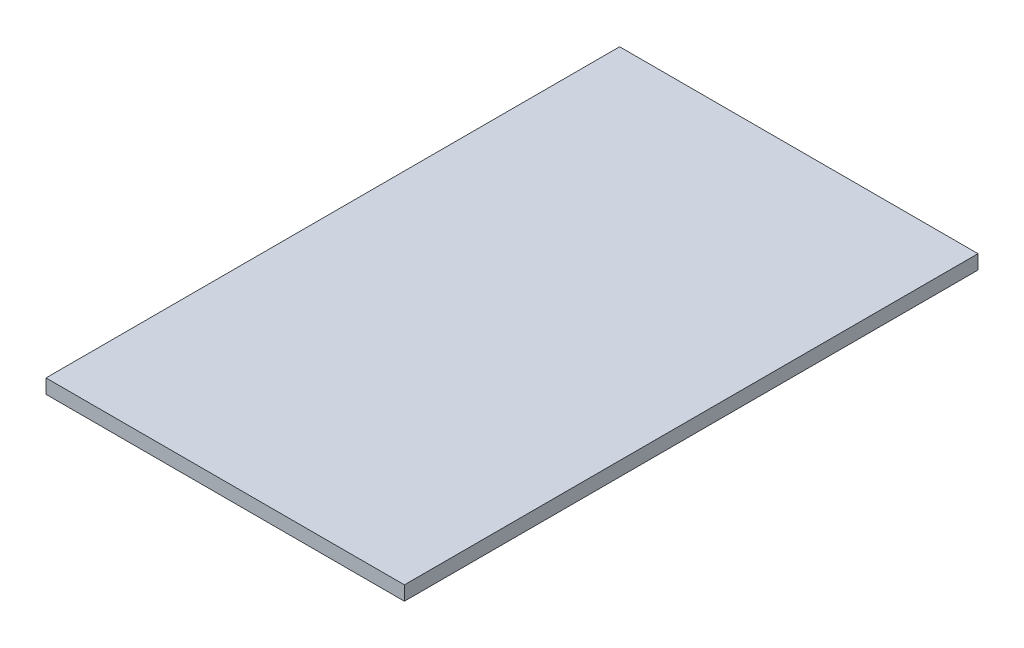
SolidWorks part; units mm, degrees
ref_plane "Front Plane" through (0, 0, 0) normal (0, 0, 1) x (1, 0, 0)
ref_plane "Top Plane" through (0, 0, 0) normal (0, 1, 0) x (1, 0, 0)
ref_plane "Right Plane" through (0, 0, 0) normal (1, 0, 0) x (0, 0, -1)
sketch "Sketch1" plane through (0, 0, 0) normal (0, 1, 0) x (1, 0, 0)
  line L1 (-35.4136, 23.6727) -> (40.1864, 23.6727)
  line L2 (-35.4136, 23.6727) -> (-35.4136, -97.3273)
  line L3 (-35.4136, -97.3273) -> (40.1864, -97.3273)
  line L4 (40.1864, 23.6727) -> (40.1864, -97.3273)
  dimension "D1" = 75.6
  dimension "D2" = 121
extrude "Boss-Extrude1" add sketch "Sketch1" along normal blind 3
